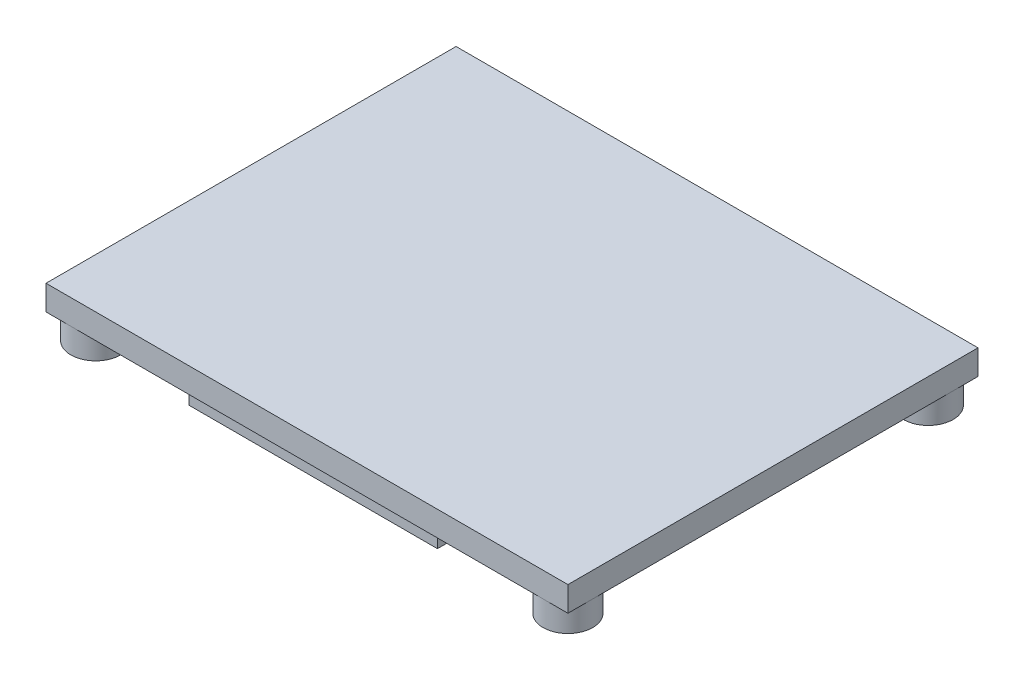
SolidWorks part; units mm, degrees
ref_plane "Front Plane" through (0, 0, 0) normal (0, 0, 1) x (1, 0, 0)
ref_plane "Top Plane" through (0, 0, 0) normal (0, 1, 0) x (1, 0, 0)
ref_plane "Right Plane" through (0, 0, 0) normal (1, 0, 0) x (0, 0, -1)
sketch "Sketch1" plane through (0, 0, 0) normal (0, 1, 0) x (1, 0, 0)
  line L1 (0, 0) -> (840, 0)
  line L2 (0, 0) -> (0, 660)
  line L3 (0, 660) -> (840, 660)
  line L4 (840, 0) -> (840, 660)
  dimension "D1" = 660
  dimension "D2" = 840
extrude "Boss-Extrude1" add sketch "Sketch1" along normal blind 40
sketch "Sketch2" plane through (0, 0, 0) normal (0, -1, 0) x (1, 0, 0)
  line L0 (0, -660) -> (0, 0) construction
  line L1 (0, 0) -> (840, 0) construction
  line L2 (840, 0) -> (840, -660) construction
  line L3 (840, -660) -> (0, -660) construction
  circle A0 centre (40, -40) radius 40
  circle A1 centre (800, -40) radius 40
  circle A2 centre (40, -620) radius 40
  circle A3 centre (800, -620) radius 40
  point P16 (0, 0)
  dimension "D1" = 80
extrude "Boss-Extrude2" add sketch "Sketch2" along normal blind 40
sketch "Sketch3" plane through (0, 0, 0) normal (0, -1, 0) x (1, 0, 0)
  line L1 (40, 0) -> (800, 0) construction
  line L2 (220, -10) -> (220, -650)
  line L3 (420, 0) -> (420, -10) construction
  line L4 (620, -10) -> (620, -650)
  line L5 (220, -10) -> (620, -10)
  line L6 (800, -660) -> (40, -660) construction
  line L7 (620, -650) -> (220, -650)
  point P5 (420, 0)
  dimension "D1" = 400
  dimension "D2" = 10
  dimension "D3" = 10
extrude "Boss-Extrude3" add sketch "Sketch3" along normal blind 25
